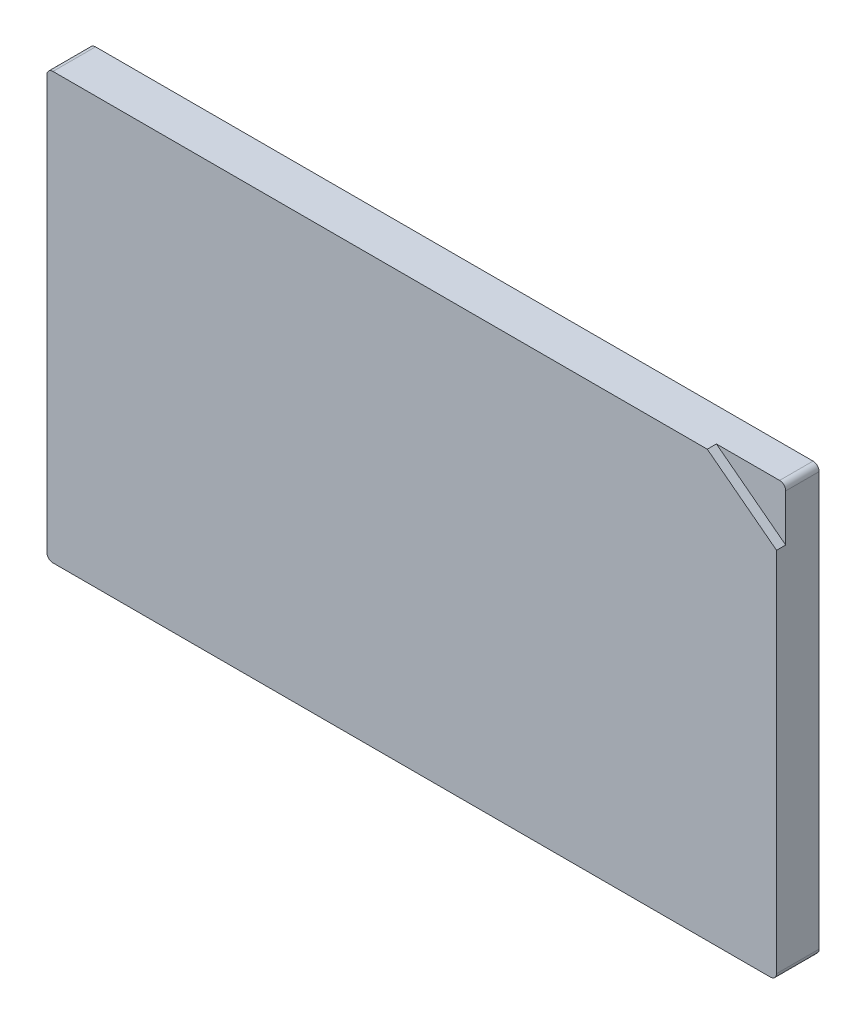
SolidWorks part; units mm, degrees
material "硅"
ref_plane "前视基准面" through (0, 0, 0) normal (0, 0, 1) x (1, 0, 0)
ref_plane "上视基准面" through (0, 0, 0) normal (0, 1, 0) x (1, 0, 0)
ref_plane "右视基准面" through (0, 0, 0) normal (1, 0, 0) x (0, 0, -1)
sketch "草图1" plane through (0, 0, 0) normal (0, 0, 1) x (1, 0, 0)
  line L1 (-7.5146, 4.9126) -> (4.4854, 4.9126)
  line L2 (-7.5146, 4.9126) -> (-7.5146, -2.0874)
  line L3 (-7.5146, -2.0874) -> (4.4854, -2.0874)
  line L4 (4.4854, 4.9126) -> (4.4854, -2.0874)
  dimension "D1" = 12
  dimension "D2" = 7
extrude "凸台-拉伸1" add sketch "草图1" along normal blind 0.7
sketch "草图2" plane through (0, 0, 0.7) normal (0, 0, 1) x (1, 0, 0)
  line L0 (3.3461, 4.9126) -> (4.4854, 4.0424)
  line L1 (4.4854, 4.9126) -> (-7.5146, 4.9126) construction
  line L2 (4.4854, -2.0874) -> (4.4854, 4.9126) construction
  line L3 (4.4854, 4.0424) -> (4.4854, 4.9126)
  line L4 (4.4854, 4.9126) -> (3.3461, 4.9126)
extrude "切除-拉伸1" cut sketch "草图2" against normal blind 0.15
fillet "圆角1" radius 0.1 4 edges at (-7.5146, 4.9126, 0.35) (-7.5146, -2.0874, 0.35) (4.4854, -2.0874, 0.35) (4.4854, 4.9126, 0.275)
